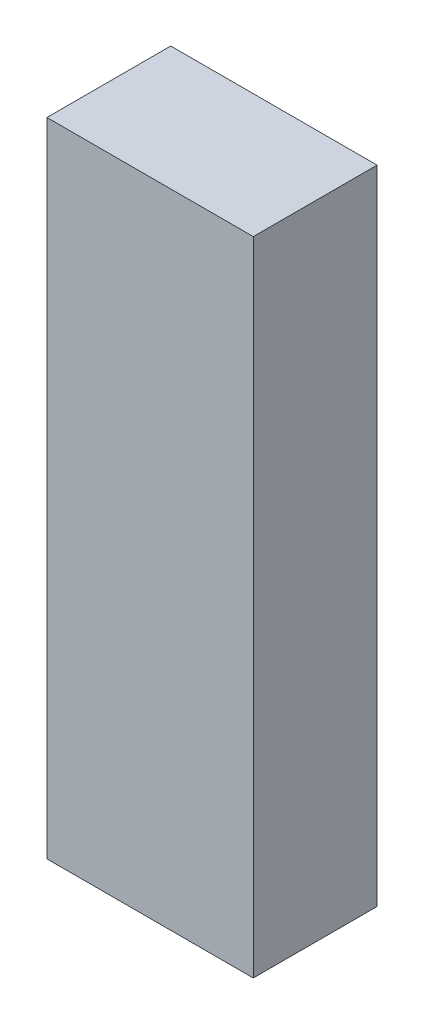
SolidWorks part; units mm, degrees
ref_plane "Front Plane" through (0, 0, 0) normal (0, 0, 1) x (1, 0, 0)
ref_plane "Top Plane" through (0, 0, 0) normal (0, 1, 0) x (1, 0, 0)
ref_plane "Right Plane" through (0, 0, 0) normal (1, 0, 0) x (0, 0, -1)
sketch "Sketch1" plane through (0, 0, 0) normal (0, 0, 1) x (1, 0, 0)
  line L0 (-264.278, 79.0362) -> (-315.078, 79.0362) construction
  line L1 (-25.4, -79.0362) -> (25.4, -79.0362)
  line L2 (-25.4, -79.0362) -> (-25.4, 79.0362)
  line L3 (-25.4, 79.0362) -> (25.4, 79.0362)
  line L4 (25.4, -79.0362) -> (25.4, 79.0362)
  line L5 (-25.4, -79.0362) -> (25.4, 79.0362) construction
  line L6 (-25.4, 79.0362) -> (25.4, -79.0362) construction
  point P0 (0, 0)
  dimension "D1" = 50.8
extrude "Boss-Extrude1" add sketch "Sketch1" along normal blind 30.48
